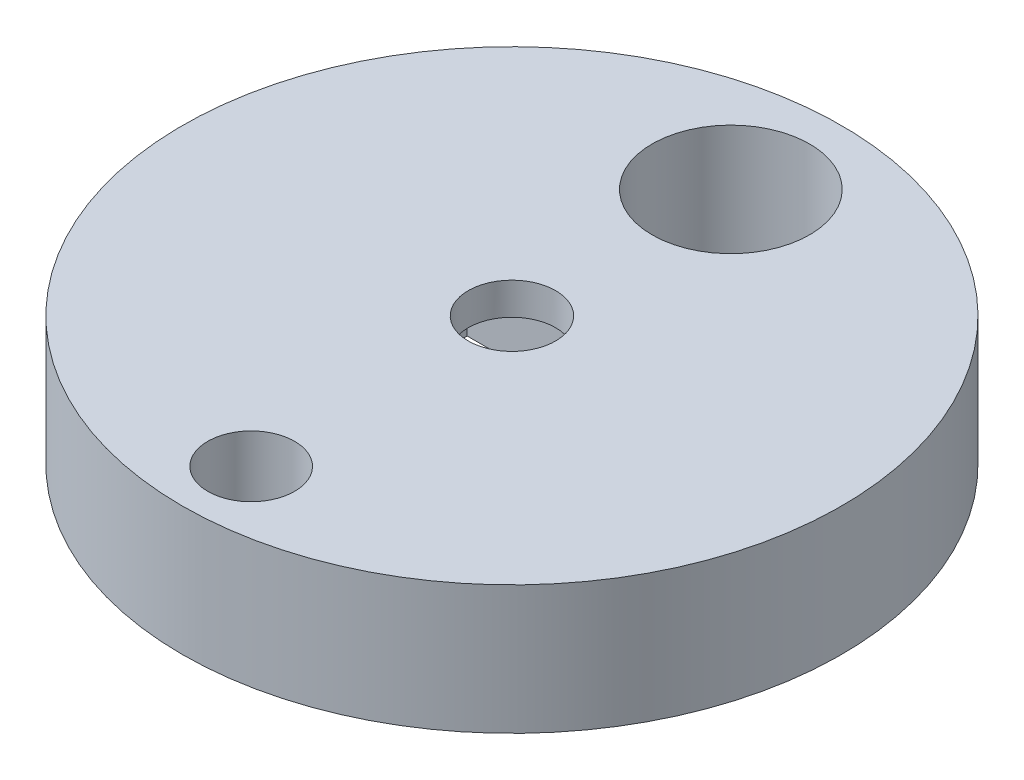
SolidWorks part; units mm, degrees
ref_plane "Front Plane" through (0, 0, 0) normal (0, 0, 1) x (1, 0, 0)
ref_plane "Top Plane" through (0, 0, 0) normal (0, 1, 0) x (1, 0, 0)
ref_plane "Right Plane" through (0, 0, 0) normal (1, 0, 0) x (0, 0, -1)
sketch "Sketch1" plane through (0, 0, 0) normal (0, 1, 0) x (1, 0, 0)
  circle A0 centre (0, 0) radius 26.035
  dimension "D1" = 52.07
extrude "Boss-Extrude1" add sketch "Sketch1" along normal blind 10.16
sketch "Sketch2" plane through (0, 10.16, 0) normal (0, 1, 0) x (1, 0, 0)
  line L0 (0, 0) -> (0, 26.035) construction
  line L1 (0, 0) -> (0, -26.035) construction
  circle A0 centre (0, 0) radius 26.035 construction
  circle A1 centre (0, 17.293) radius 6.223
  circle A3 centre (0, -20.5986) radius 3.429
  circle A4 centre (0, 0) radius 3.45
  dimension "D1" = 12.446
  dimension "D2" = 6.858
  dimension "D3" = 6.9
extrude "Cut-Extrude1" cut sketch "Sketch2" against normal through all
sketch "Sketch3" plane through (0, 0, 0) normal (0, -1, 0) x (1, 0, 0)
  line L0 (0, 0) -> (0, 11.536)
  line L1 (-10.541, 11.536) -> (10.541, 11.536)
  line L2 (10.541, 11.536) -> (10.541, -7.006)
  line L3 (10.541, -7.006) -> (-10.541, -7.006)
  line L4 (-10.541, -7.006) -> (-10.541, 11.536)
  line L5 (0, -17.293) -> (0, 0) construction
  line L6 (0, -3.45) -> (10.541, -3.45) construction
  circle A1 centre (0, 0) radius 3.45 construction
  point P8 (0, -7.006)
  dimension "D1" = 18.542
  dimension "D2" = 21.082
  dimension "D3" = 3.556
extrude "Cut-Extrude2" cut sketch "Sketch3" against normal blind 7.62
